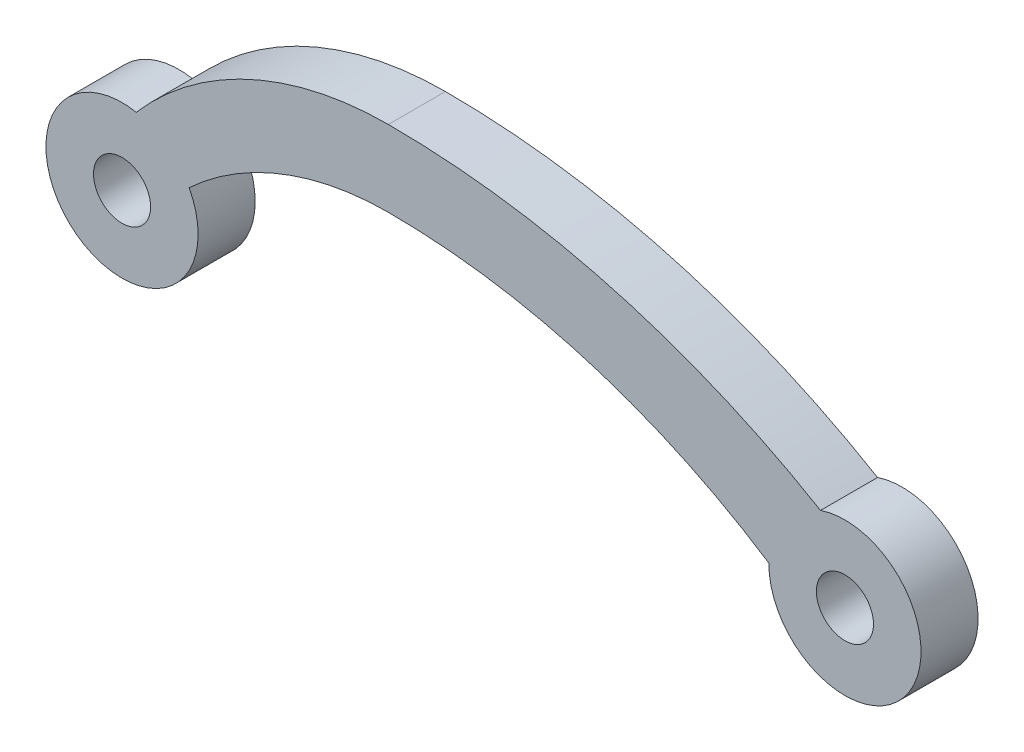
SolidWorks part; units mm, degrees
material "Acrílico (Impacto medio-alto)"
ref_plane "Alzado" through (0, 0, 0) normal (0, 0, 1) x (1, 0, 0)
ref_plane "Planta" through (0, 0, 0) normal (0, 1, 0) x (1, 0, 0)
ref_plane "Vista lateral" through (0, 0, 0) normal (1, 0, 0) x (0, 0, -1)
sketch "Croquis1" plane through (0, 0, 0) normal (0, 0, 1) x (1, 0, 0)
  line L0 (14, 6) -> (14, 10)
  circle A0 centre (0, 0) radius 4
  circle A1 centre (0, 0) radius 1.5
  circle A2 centre (14, 0) radius 6
  circle A3 centre (38, 0) radius 1.5
  circle A4 centre (38, 0) radius 4
  circle A5 centre (0, 0) radius 3
  circle A6 centre (38, 0) radius 3
  arc A7 (14, 10) -> (38, 3) centre (14, -34.6429) cw
  arc A8 (14, 6) -> (38, -3) centre (14, -30.5) cw
  arc A9 (14, 10) -> (0, 3) centre (14, -7.5) ccw
  arc A10 (14, 6) -> (0, -3) centre (14, -9.3889) ccw
  dimension "D1" = 8
  dimension "D2" = 3
  dimension "D3" = 12
  dimension "D6" = 8
  dimension "D7" = 3
  dimension "D8" = 6
  dimension "D9" = 6
  dimension "D4" = 14
  dimension "D5" = 4
  dimension "D10" = 38
extrude "Saliente-Extruir1" add sketch "Croquis1" along normal blind 3 contours L0 A8 A4 A7 | A10 L0 A9 A0 | A1 | A3
